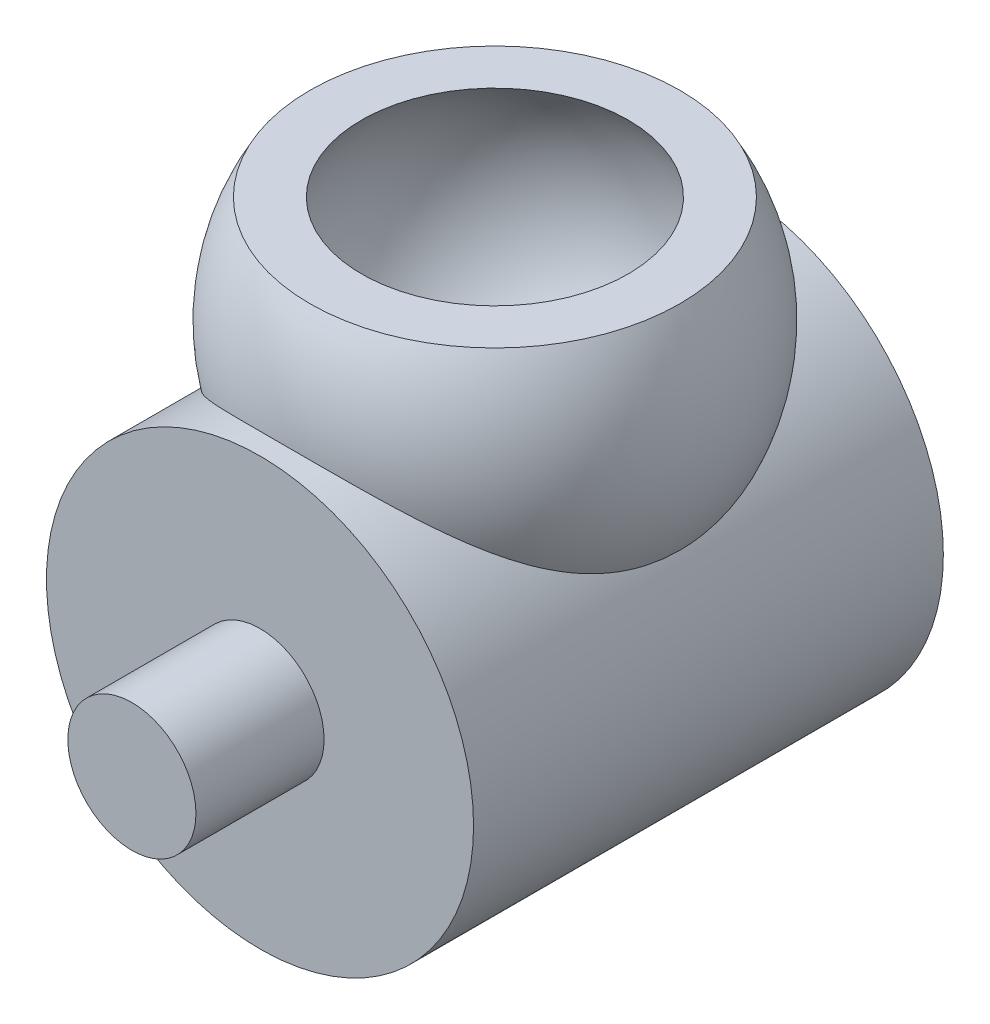
SolidWorks part; units mm, degrees
ref_plane "Front Plane" through (0, 0, 0) normal (0, 0, 1) x (1, 0, 0)
ref_plane "Top Plane" through (0, 0, 0) normal (0, 1, 0) x (1, 0, 0)
ref_plane "Right Plane" through (0, 0, 0) normal (1, 0, 0) x (0, 0, -1)
sketch "Sketch1" plane through (0, 0, 0) normal (0, 0, 1) x (1, 0, 0)
  circle A0 centre (0, 0) radius 10
  dimension "D1" = 20
extrude "Boss-Extrude1" add sketch "Sketch1" along normal blind 22
sketch "Sketch2" plane through (0, 0, 22) normal (0, 0, 1) x (1, 0, 0)
  circle A0 centre (0, 0) radius 3
  dimension "D1" = 6
extrude "Boss-Extrude2" add sketch "Sketch2" along normal blind 6
sketch "Sketch6" plane through (0, 0, 0) normal (1, 0, 0) x (0, 0, -1)
  line L0 (0, 0) -> (-22, 0) construction
  line L1 (-22, 10) -> (-22, -10) construction
  line L2 (-11, 0) -> (-11, 10) construction
  line L3 (0, 10) -> (-22, 10) construction
  line L4 (-11, 0) -> (-11, 10)
  line L5 (-11, 10) -> (-1, 10)
  arc A0 (-1, 10) -> (-11, 0) centre (-11, 10) cw
  dimension "D1" = 10
revolve "Cut-Revolve3" cut sketch "Sketch6" angle 360 about L4
sketch "Sketch7" plane through (0, 0, 0) normal (1, 0, 0) x (0, 0, -1)
  line L0 (0, 0) -> (-22, 0) construction
  line L1 (-22, 3) -> (-22, -3) construction
  line L2 (-22, 10) -> (0, 10) construction
  line L3 (-11, 0) -> (-11, 10) construction
  line L4 (-4.755, 15) -> (-2.3397, 15)
  line L5 (-11, 0) -> (-11, 2)
  line L6 (-2.3397, 15) -> (-11, 10) construction
  arc A0 (-2.3397, 15) -> (-11, 0) centre (-11, 10) cw
  arc A1 (-4.755, 15) -> (-11, 2) centre (-11, 10) cw
  dimension "D1" = 10
  dimension "D2" = 8
  dimension "D3" = 60
revolve "Revolve1" add sketch "Sketch7" angle 360 about L3
